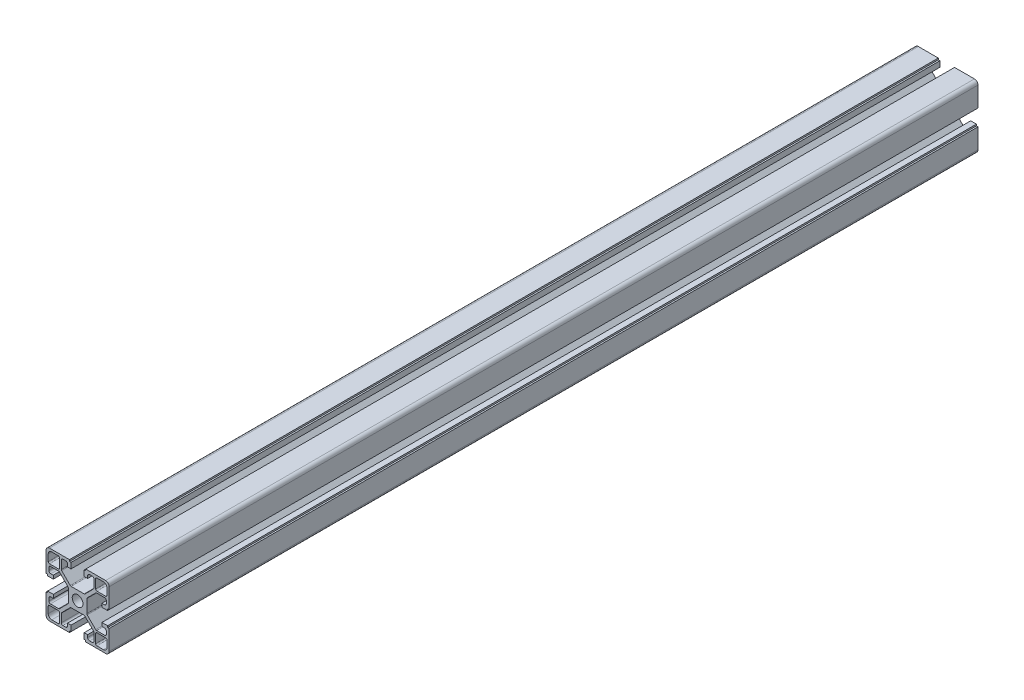
SolidWorks part; units mm, degrees
material "6063-T5"
ref_plane "Front Plane" through (0, 0, 0) normal (0, 0, 1) x (1, 0, 0)
ref_plane "Top Plane" through (0, 0, 0) normal (0, 1, 0) x (1, 0, 0)
ref_plane "Right Plane" through (0, 0, 0) normal (1, 0, 0) x (0, 0, -1)
sketch "Sketch1" plane through (0, 0, 0) normal (0, 0, 1) x (1, 0, 0)
  line L4 (20, 17.75) -> (20, 5.15)
  line L5 (0, -17.7813) -> (0, 18.2) construction
  line L6 (0, 0) -> (38.8613, 0) construction
  line L8 (18.6, 16.35) -> (18.6, 12.2)
  line L10 (11.4, 17.8) -> (11.4, 12.2)
  line L11 (-4.1, 5.85) -> (4.1, 5.85)
  line L14 (5.85, 4.1089) -> (5.85, -4.1089)
  line L17 (12.2, 11.4) -> (17.8, 11.4)
  line L24 (4.15, 19) -> (4.15, 15.4)
  line L25 (4.15, 15.4) -> (6.35, 15.4)
  line L26 (6.35, 15.4) -> (6.35, 16.95)
  line L27 (10.3, 17.2) -> (10.3, 12.0545)
  line L28 (10.0659, 11.489) -> (4.6659, 6.0845)
  line L29 (6.0841, 4.6743) -> (11.4708, 10.0655)
  line L30 (12.0367, 10.3) -> (17.2, 10.3)
  line L31 (18.2, 9.3) -> (18.2, 7.6)
  line L32 (16.95, 6.35) -> (15.4, 6.35)
  line L33 (15.4, 6.35) -> (15.4, 4.15)
  line L34 (15.4, 4.15) -> (19, 4.15)
  line L35 (18.6, 18.6) -> (18.6, -18.6) construction
  line L36 (-18.6, 18.6) -> (18.6, 18.6) construction
  line L37 (-20, 20) -> (20, 20) construction
  line L38 (20, 20) -> (20, -20) construction
  line L40 (7.6, 18.2) -> (9.3, 18.2)
  line L42 (4.15, 19) -> (5.15, 19)
  line L43 (5.15, 19) -> (5.15, 20)
  line L56 (-18.6, 18.6) -> (-18.6, -18.6) construction
  line L57 (-20, 20) -> (-20, -20) construction
  line L60 (5.15, 20) -> (17.75, 20)
  line L91 (-18.6, -18.6) -> (18.6, -18.6) construction
  line L92 (-20, -20) -> (20, -20) construction
  line L93 (12.2, 18.6) -> (16.35, 18.6)
  line L94 (17.9399, 17.9421) -> (20, 20) construction
  line L95 (0, 0) -> (11.4, 11.4094) construction
  line L101 (19, 4.15) -> (19, 5.15)
  line L102 (19, 5.15) -> (20, 5.15)
  line L104 (-5.85, 4.1089) -> (-5.85, -4.1089)
  line L105 (-19, 5.15) -> (-20, 5.15)
  line L106 (-19, 4.15) -> (-19, 5.15)
  line L107 (-12.2, 18.6) -> (-16.35, 18.6)
  line L108 (-5.15, 20) -> (-17.75, 20)
  line L109 (-5.15, 19) -> (-5.15, 20)
  line L110 (-4.15, 19) -> (-5.15, 19)
  line L111 (-7.6, 18.2) -> (-9.3, 18.2)
  line L112 (-15.4, 4.15) -> (-19, 4.15)
  line L113 (-15.4, 6.35) -> (-15.4, 4.15)
  line L114 (-16.95, 6.35) -> (-15.4, 6.35)
  line L115 (-18.2, 9.3) -> (-18.2, 7.6)
  line L116 (-12.0367, 10.3) -> (-17.2, 10.3)
  line L117 (-6.0841, 4.6743) -> (-11.4708, 10.0655)
  line L118 (-10.0659, 11.489) -> (-4.6659, 6.0845)
  line L119 (-10.3, 17.2) -> (-10.3, 12.0545)
  line L120 (-6.35, 15.4) -> (-6.35, 16.95)
  line L121 (-4.15, 15.4) -> (-6.35, 15.4)
  line L122 (-4.15, 19) -> (-4.15, 15.4)
  line L123 (-12.2, 11.4) -> (-17.8, 11.4)
  line L124 (-11.4, 17.8) -> (-11.4, 12.2)
  line L125 (-18.6, 16.35) -> (-18.6, 12.2)
  line L126 (-20, 17.75) -> (-20, 5.15)
  line L127 (-20, -17.75) -> (-20, -5.15)
  line L128 (-18.6, -16.35) -> (-18.6, -12.2)
  line L129 (-11.4, -17.8) -> (-11.4, -12.2)
  line L130 (-12.2, -11.4) -> (-17.8, -11.4)
  line L131 (-4.15, -19) -> (-4.15, -15.4)
  line L132 (-4.15, -15.4) -> (-6.35, -15.4)
  line L133 (-6.35, -15.4) -> (-6.35, -16.95)
  line L134 (-10.3, -17.2) -> (-10.3, -12.0545)
  line L135 (-10.0659, -11.489) -> (-4.6659, -6.0845)
  line L136 (-6.0841, -4.6743) -> (-11.4708, -10.0655)
  line L137 (-12.0367, -10.3) -> (-17.2, -10.3)
  line L138 (-18.2, -9.3) -> (-18.2, -7.6)
  line L139 (-16.95, -6.35) -> (-15.4, -6.35)
  line L140 (-15.4, -6.35) -> (-15.4, -4.15)
  line L141 (-15.4, -4.15) -> (-19, -4.15)
  line L142 (-7.6, -18.2) -> (-9.3, -18.2)
  line L143 (-4.15, -19) -> (-5.15, -19)
  line L144 (-5.15, -19) -> (-5.15, -20)
  line L145 (-5.15, -20) -> (-17.75, -20)
  line L146 (-12.2, -18.6) -> (-16.35, -18.6)
  line L147 (-19, -4.15) -> (-19, -5.15)
  line L148 (-19, -5.15) -> (-20, -5.15)
  line L149 (19, -5.15) -> (20, -5.15)
  line L150 (19, -4.15) -> (19, -5.15)
  line L151 (12.2, -18.6) -> (16.35, -18.6)
  line L152 (5.15, -20) -> (17.75, -20)
  line L153 (5.15, -19) -> (5.15, -20)
  line L154 (4.15, -19) -> (5.15, -19)
  line L155 (7.6, -18.2) -> (9.3, -18.2)
  line L156 (15.4, -4.15) -> (19, -4.15)
  line L157 (15.4, -6.35) -> (15.4, -4.15)
  line L158 (16.95, -6.35) -> (15.4, -6.35)
  line L159 (18.2, -9.3) -> (18.2, -7.6)
  line L160 (12.0367, -10.3) -> (17.2, -10.3)
  line L161 (6.0841, -4.6743) -> (11.4708, -10.0655)
  line L162 (10.0659, -11.489) -> (4.6659, -6.0845)
  line L163 (10.3, -17.2) -> (10.3, -12.0545)
  line L164 (6.35, -15.4) -> (6.35, -16.95)
  line L165 (4.15, -15.4) -> (6.35, -15.4)
  line L166 (4.15, -19) -> (4.15, -15.4)
  line L167 (12.2, -11.4) -> (17.8, -11.4)
  line L168 (-4.1, -5.85) -> (4.1, -5.85)
  line L169 (11.4, -17.8) -> (11.4, -12.2)
  line L170 (18.6, -16.35) -> (18.6, -12.2)
  line L171 (20, -17.75) -> (20, -5.15)
  circle A0 centre (0, 0) radius 3.4
  arc A7 (16.35, 18.6) -> (18.6, 16.35) centre (16.35, 16.35) cw
  arc A8 (20, 17.75) -> (17.75, 20) centre (17.75, 17.75) ccw
  arc A9 (6.35, 16.95) -> (7.6, 18.2) centre (7.6, 16.95) cw
  arc A10 (18.2, 7.6) -> (16.95, 6.35) centre (16.95, 7.6) cw
  arc A11 (17.2, 10.3) -> (18.2, 9.3) centre (17.2, 9.3) cw
  arc A12 (9.3, 18.2) -> (10.3, 17.2) centre (9.3, 17.2) cw
  arc A13 (4.6659, 6.0845) -> (4.1, 5.85) centre (4.1, 6.65) cw
  arc A14 (6.0841, 4.6743) -> (5.85, 4.1089) centre (6.65, 4.1089) ccw
  arc A15 (17.8, 11.4) -> (18.6, 12.2) centre (17.8, 12.2) ccw
  arc A16 (12.2, 18.6) -> (11.4, 17.8) centre (12.2, 17.8) ccw
  arc A17 (11.4, 12.2) -> (12.2, 11.4) centre (12.2, 12.2) ccw
  arc A18 (11.4708, 10.0655) -> (12.0367, 10.3) centre (12.0367, 9.5) cw
  arc A19 (10.3, 12.0545) -> (10.0659, 11.489) centre (9.5, 12.0545) cw
  arc A20 (-10.3, 12.0545) -> (-10.0659, 11.489) centre (-9.5, 12.0545) ccw
  arc A21 (-11.4708, 10.0655) -> (-12.0367, 10.3) centre (-12.0367, 9.5) ccw
  arc A22 (-11.4, 12.2) -> (-12.2, 11.4) centre (-12.2, 12.2) cw
  arc A23 (-12.2, 18.6) -> (-11.4, 17.8) centre (-12.2, 17.8) cw
  arc A24 (-17.8, 11.4) -> (-18.6, 12.2) centre (-17.8, 12.2) cw
  arc A25 (-6.0841, 4.6743) -> (-5.85, 4.1089) centre (-6.65, 4.1089) cw
  arc A26 (-4.6659, 6.0845) -> (-4.1, 5.85) centre (-4.1, 6.65) ccw
  arc A27 (-9.3, 18.2) -> (-10.3, 17.2) centre (-9.3, 17.2) ccw
  arc A28 (-17.2, 10.3) -> (-18.2, 9.3) centre (-17.2, 9.3) ccw
  arc A29 (-18.2, 7.6) -> (-16.95, 6.35) centre (-16.95, 7.6) ccw
  arc A30 (-6.35, 16.95) -> (-7.6, 18.2) centre (-7.6, 16.95) ccw
  arc A31 (-20, 17.75) -> (-17.75, 20) centre (-17.75, 17.75) cw
  arc A32 (-16.35, 18.6) -> (-18.6, 16.35) centre (-16.35, 16.35) ccw
  arc A33 (-16.35, -18.6) -> (-18.6, -16.35) centre (-16.35, -16.35) cw
  arc A34 (-20, -17.75) -> (-17.75, -20) centre (-17.75, -17.75) ccw
  arc A35 (-6.35, -16.95) -> (-7.6, -18.2) centre (-7.6, -16.95) cw
  arc A36 (-18.2, -7.6) -> (-16.95, -6.35) centre (-16.95, -7.6) cw
  arc A37 (-17.2, -10.3) -> (-18.2, -9.3) centre (-17.2, -9.3) cw
  arc A38 (-9.3, -18.2) -> (-10.3, -17.2) centre (-9.3, -17.2) cw
  arc A39 (-4.6659, -6.0845) -> (-4.1, -5.85) centre (-4.1, -6.65) cw
  arc A40 (-6.0841, -4.6743) -> (-5.85, -4.1089) centre (-6.65, -4.1089) ccw
  arc A41 (-17.8, -11.4) -> (-18.6, -12.2) centre (-17.8, -12.2) ccw
  arc A42 (-12.2, -18.6) -> (-11.4, -17.8) centre (-12.2, -17.8) ccw
  arc A43 (-11.4, -12.2) -> (-12.2, -11.4) centre (-12.2, -12.2) ccw
  arc A44 (-11.4708, -10.0655) -> (-12.0367, -10.3) centre (-12.0367, -9.5) cw
  arc A45 (-10.3, -12.0545) -> (-10.0659, -11.489) centre (-9.5, -12.0545) cw
  arc A46 (10.3, -12.0545) -> (10.0659, -11.489) centre (9.5, -12.0545) ccw
  arc A47 (11.4708, -10.0655) -> (12.0367, -10.3) centre (12.0367, -9.5) ccw
  arc A48 (11.4, -12.2) -> (12.2, -11.4) centre (12.2, -12.2) cw
  arc A49 (12.2, -18.6) -> (11.4, -17.8) centre (12.2, -17.8) cw
  arc A50 (17.8, -11.4) -> (18.6, -12.2) centre (17.8, -12.2) cw
  arc A51 (6.0841, -4.6743) -> (5.85, -4.1089) centre (6.65, -4.1089) cw
  arc A52 (4.6659, -6.0845) -> (4.1, -5.85) centre (4.1, -6.65) ccw
  arc A53 (9.3, -18.2) -> (10.3, -17.2) centre (9.3, -17.2) ccw
  arc A54 (17.2, -10.3) -> (18.2, -9.3) centre (17.2, -9.3) ccw
  arc A55 (18.2, -7.6) -> (16.95, -6.35) centre (16.95, -7.6) ccw
  arc A56 (6.35, -16.95) -> (7.6, -18.2) centre (7.6, -16.95) ccw
  arc A57 (20, -17.75) -> (17.75, -20) centre (17.75, -17.75) cw
  arc A58 (16.35, -18.6) -> (18.6, -16.35) centre (16.35, -16.35) ccw
  point P0 (0, 0)
  point P16 (-5.85, 0)
  point P66 (0, 5.85)
  point P120 (5.85, 0)
  point P218 (0, -5.85)
  dimension "D5" = 6.8
  dimension "D6" = 1.4
  dimension "D15" = 5.85
  dimension "D44" = 2.25
  dimension "D25" = 1.25
  dimension "D26" = 1
  dimension "D27" = 0.8
  dimension "D7" = 1.1
  dimension "D8" = 1.1
  dimension "D9" = 1.8
  dimension "D10" = 2.2
  dimension "D11" = 4.6
  dimension "D12" = 1.8
  dimension "D13" = 2.2
  dimension "D14" = 5.85
  dimension "D16" = 1.4
  dimension "D17" = 4.15
  dimension "D18" = 1
  dimension "D19" = 1
  dimension "D20" = 10.3
  dimension "D21" = 4.15
  dimension "D22" = 2
  dimension "D23" = 45.024
  dimension "D24" = 1
  dimension "D41" = 10.3
  dimension "D60" = 14.15
  dimension "D73" = 1
  dimension "D74" = 1
  dimension "D82" = 14.15
  dimension "D3" = 4.6
extrude "Boss-Extrude1" add sketch "Sketch1" along normal blind 713
sketch "Sketch2" plane through (0, 20, 0) normal (0, 1, 0) x (1, 0, 0)
  line L0 (-20, -713) -> (-20, 0) construction
  line L1 (-20, -550) -> (20, -550)
  line L2 (-20, -550) -> (-20, -713)
  line L3 (-20, -713) -> (20, -713)
  line L4 (20, -550) -> (20, -713)
  line L5 (-5.15, 0) -> (-17.75, 0) construction
  dimension "D1" = 550
extrude "Cut-Extrude1" cut sketch "Sketch2" against normal through all
